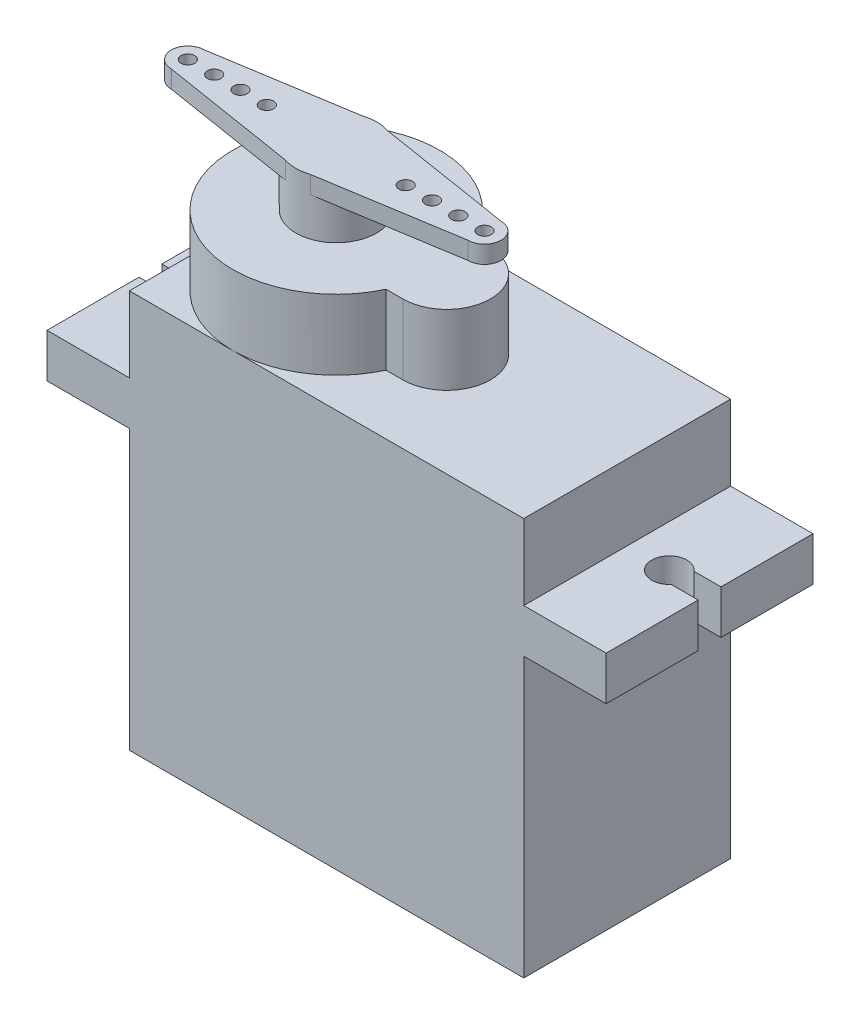
SolidWorks part; units mm, degrees
ref_plane "Alzado" through (0, 0, 0) normal (0, 0, 1) x (1, 0, 0)
ref_plane "Planta" through (0, 0, 0) normal (0, 1, 0) x (1, 0, 0)
ref_plane "Vista lateral" through (0, 0, 0) normal (1, 0, 0) x (0, 0, -1)
sketch "Croquis1" plane through (0, 0, 0) normal (0, 0, 1) x (1, 0, 0)
  line L0 (-10.84, -12.5133) -> (11.66, -12.5133)
  line L1 (11.66, -12.5133) -> (11.66, 3.3867)
  line L2 (11.66, 3.3867) -> (16.36, 3.3867)
  line L3 (16.36, 3.3867) -> (16.36, 5.8867)
  line L4 (16.36, 5.8867) -> (11.66, 5.8867)
  line L5 (11.66, 5.8867) -> (11.66, 10.1867)
  line L6 (11.66, 10.1867) -> (-10.84, 10.1867)
  line L7 (-10.84, 10.1867) -> (-10.84, 5.8867)
  line L8 (-10.84, 5.8867) -> (-15.54, 5.8867)
  line L9 (-15.54, 5.8867) -> (-15.54, 3.3867)
  line L10 (-15.54, 3.3867) -> (-10.84, 3.3867)
  line L11 (-10.84, 3.3867) -> (-10.84, -12.5133)
  dimension "D1" = 22.5
  dimension "D2" = 15.9
  dimension "D3" = 2.5
  dimension "D4" = 22.7
  dimension "D5" = 22.5
  dimension "D6" = 4.7
  dimension "D7" = 4.7
extrude "Saliente-Extruir1" add sketch "Croquis1" along normal blind 11.8
sketch "Croquis2" plane through (0, 10.1867, 0) normal (0, 1, 0) x (1, 0, 0)
  line L0 (11.66, 0) -> (-10.84, 0) construction
  line L1 (-10.84, -11.8) -> (-10.84, 0) construction
  line L2 (1.36, -3.4) -> (0.4041, -3.4)
  line L3 (1.36, -8.4) -> (0.4041, -8.4)
  arc A0 (0.4041, -3.4) -> (0.4041, -8.4) centre (-4.94, -5.9) ccw
  arc A1 (1.36, -8.4) -> (1.36, -3.4) centre (1.36, -5.9) ccw
  circle A2 centre (-4.94, -5.9) radius 2.3
  dimension "D1" = 4.6
  dimension "D2" = 11.8
  dimension "D3" = 5
  dimension "D4" = 6.3
extrude "Saliente-Extruir2" add sketch "Croquis2" along normal blind 4
sketch "Croquis3" plane through (0, 10.1867, 0) normal (0, 1, 0) x (1, 0, 0)
  circle A1 centre (-4.94, -5.9) radius 2.3
  circle A2 centre (-4.94, -5.9) radius 2.3
  dimension "D1" = 0
extrude "Saliente-Extruir3" add sketch "Croquis3" along normal blind 7.2
sketch "Croquis4" plane through (0, 5.8867, 0) normal (0, 1, 0) x (1, 0, 0)
  line L0 (16.36, -11.8) -> (16.36, 0) construction
  line L1 (-15.54, -11.8) -> (-15.54, 0) construction
  line L2 (16.36, 0) -> (11.66, 0) construction
  line L3 (16.36, -5.25) -> (16.36, -6.55)
  line L4 (16.36, -5.25) -> (14.8199, -5.25)
  line L5 (16.36, -6.55) -> (14.8199, -6.55)
  line L6 (-15.54, -6.55) -> (-15.54, -5.25)
  line L7 (-13.9999, -5.25) -> (-15.54, -5.25)
  line L8 (-13.9999, -6.55) -> (-15.54, -6.55)
  arc A0 (14.8199, -5.25) -> (14.8199, -6.55) centre (14.06, -5.9) ccw
  arc A1 (-13.9999, -6.55) -> (-13.9999, -5.25) centre (-13.24, -5.9) ccw
  point P11 (16.36, -5.9)
  point P12 (14.6404, -5.9)
  dimension "D6" = 2
  dimension "D1" = 2.3
  dimension "D2" = 2.3
  dimension "D3" = 5.9
extrude "Cortar-Extruir1" cut sketch "Croquis4" against normal blind 7.2
sketch "Croquis5" plane through (0, 17.3867, 0) normal (0, 1, 0) x (1, 0, 0)
  line L0 (3.5228, -4.9591) -> (-4.94, -3.6)
  line L6 (3.5228, -6.8409) -> (-4.94, -8.2)
  line L9 (-13.4028, -6.8409) -> (-4.94, -8.2)
  line L10 (-13.4028, -4.9591) -> (-4.94, -3.6)
  arc A0 (3.5228, -6.8409) -> (3.5228, -4.9591) centre (3.5228, -5.9) ccw
  circle A1 centre (3.5228, -5.9) radius 0.3874
  circle A17 centre (2.0228, -5.9) radius 0.3874
  circle A18 centre (0.5228, -5.9) radius 0.3874
  circle A19 centre (-0.9772, -5.9) radius 0.3874
  arc A25 (-13.4028, -4.9591) -> (-13.4028, -6.8409) centre (-13.4028, -5.9) ccw
  circle A26 centre (-13.4028, -5.9) radius 0.3874
  circle A27 centre (-11.9028, -5.9) radius 0.3874
  circle A28 centre (-10.4028, -5.9) radius 0.3874
  circle A29 centre (-8.9028, -5.9) radius 0.3874
  point P56 (-4.94, -5.9)
extrude "Saliente-Extruir4" add sketch "Croquis5" against normal blind 1
